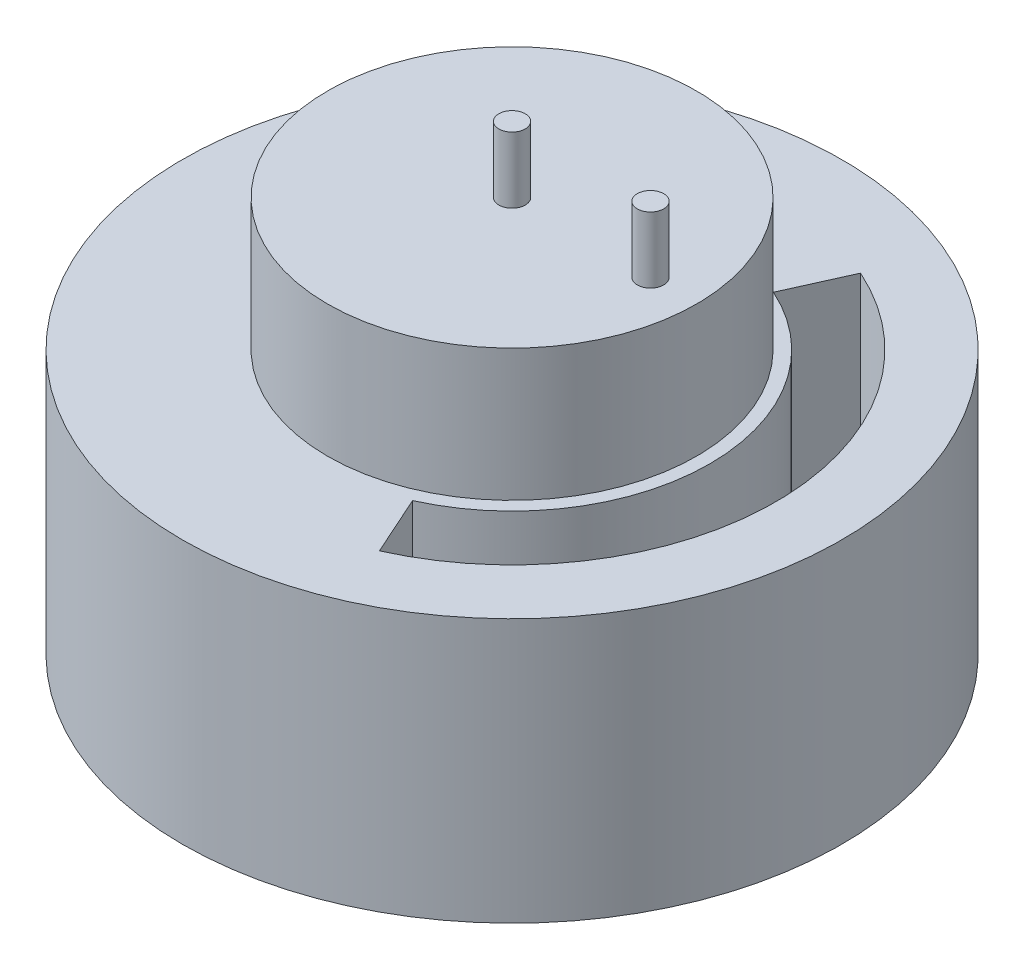
SolidWorks part; units mm, degrees
ref_plane "Plano frontal" through (0, 0, 0) normal (0, 0, 1) x (1, 0, 0)
ref_plane "Plano superior" through (0, 0, 0) normal (0, 1, 0) x (1, 0, 0)
ref_plane "Plano direito" through (0, 0, 0) normal (1, 0, 0) x (0, 0, -1)
sketch "Esboço1" plane through (0, 0, 0) normal (0, 1, 0) x (1, 0, 0)
  line L0 (0, 0) -> (-10, 0) construction
  line L1 (0, 0) -> (10, 0) construction
  line L2 (-10, 0) -> (-10, -17.3205) construction
  line L3 (10, 0) -> (10, -17.3205) construction
  line L4 (10, -27.2235) -> (-10, -27.2235) construction
  line L9 (-10, -22.9129) -> (-10, -27.2235) construction
  line L11 (10, -22.9129) -> (10, -27.2235) construction
  arc A1 (12.5, -21.6506) -> (-12.5, -21.6506) centre (0, 0) ccw
  circle A3 centre (0, 0) radius 25
extrude "Ressalto-extrusão2" add sketch "Esboço1" along normal blind 20
ref_plane "Plano1" through (0, 20, 0) normal (0, 1, 0) x (1, 0, 0)
sketch "Esboço3" plane through (0, 20, 0) normal (0, 1, 0) x (1, 0, 0)
  circle A0 centre (0, 0) radius 14
extrude "Boss-Extrude1" add sketch "Esboço3" along normal blind 10
sketch "Sketch1" plane through (0, 20, 0) normal (0, 1, 0) x (1, 0, 0)
  circle A0 centre (0, 0) radius 20
  circle A1 centre (0, 0) radius 25
ref_plane "Plane1" through (0, 30, 0) normal (0, 1, 0) x (1, 0, 0)
sketch "Sketch2" plane through (0, 30, 0) normal (0, 1, 0) x (1, 0, 0)
  line L0 (1, 0) -> (10.5, 0) construction
  circle A0 centre (0, 0) radius 1
  circle A1 centre (10.5, 0) radius 1
extrude "Boss-Extrude2" add sketch "Sketch2" along normal blind 5
ref_plane "Plane2" through (0, 20, 0) normal (0, 1, 0) x (1, 0, 0)
sketch "Sketch3" plane through (0, 20, 0) normal (0, 1, 0) x (1, 0, 0)
  line L0 (0, 0) -> (15, 0) construction
  line L1 (0, 0) -> (8.1857, -18.2481) construction
  line L2 (0, 0) -> (8.1857, 18.2481) construction
  line L3 (8.1857, -18.2481) -> (6.1393, -13.6861)
  line L4 (8.1857, 18.2481) -> (6.1393, 13.6861)
  arc A0 (6.1393, -13.6861) -> (6.1393, 13.6861) centre (0, 0) ccw
  arc A1 (8.1857, -18.2481) -> (8.1857, 18.2481) centre (0, 0) ccw
  dimension "D1" = 65.84
extrude "Cut-Extrude2" cut sketch "Sketch3" against normal up to surface (20 mm away) up to face at (0, 0, 25)
